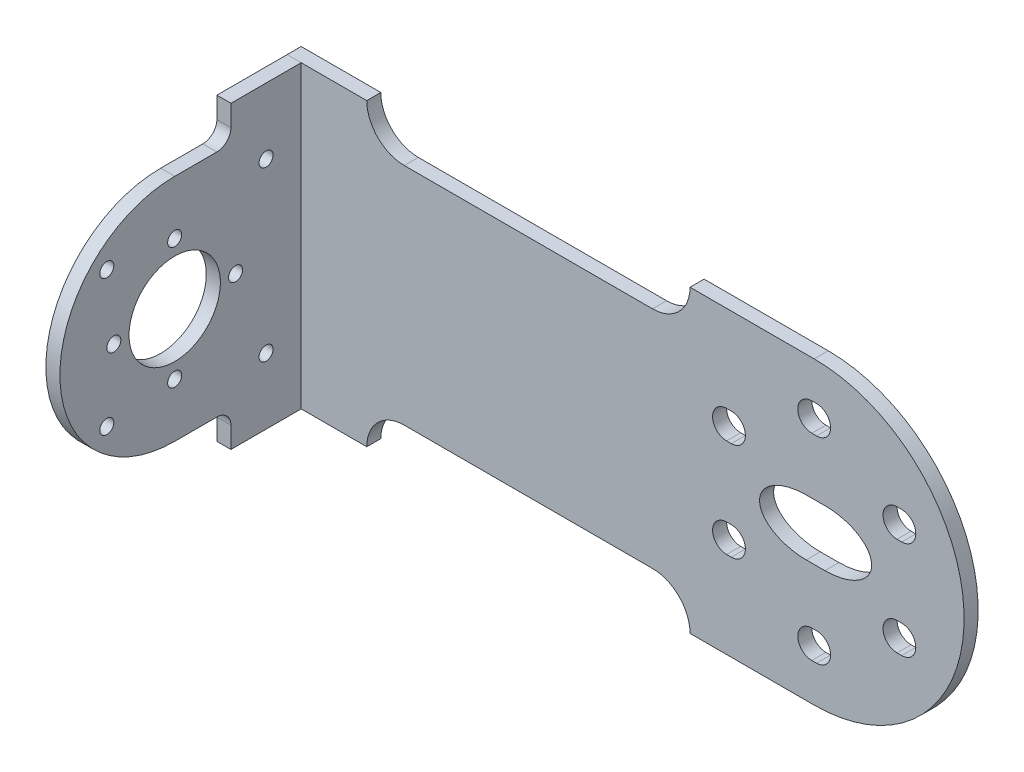
SolidWorks part; units mm, degrees
material "1060 Alloy"
ref_plane "Front Plane" through (0, 0, 0) normal (0, 0, 1) x (1, 0, 0)
ref_plane "Top Plane" through (0, 0, 0) normal (0, 1, 0) x (1, 0, 0)
ref_plane "Right Plane" through (0, 0, 0) normal (1, 0, 0) x (0, 0, -1)
sketch "Sketch1" plane through (0, 0, 0) normal (0, 0, 1) x (1, 0, 0)
  line L0 (-112.5, 32) -> (0, 32)
  line L1 (-112.5, -32) -> (0, -32)
  line L2 (17.6865, 10.5) -> (18.6865, 10.5) construction
  line L3 (-112.5, 32) -> (-112.5, -32)
  line L4 (-113, -33) -> (-113, 33) construction
  line L7 (17.6865, 13.5) -> (18.6865, 13.5)
  line L8 (17.6865, 7.5) -> (18.6865, 7.5)
  line L9 (17.6865, -10.5) -> (18.6865, -10.5) construction
  line L10 (17.6865, -7.5) -> (18.6865, -7.5)
  line L11 (17.6865, -13.5) -> (18.6865, -13.5)
  line L12 (-0.5, -21) -> (0.5, -21) construction
  line L13 (-0.5, -18) -> (0.5, -18)
  line L14 (-0.5, -24) -> (0.5, -24)
  line L15 (-18.6865, -10.5) -> (-17.6865, -10.5) construction
  line L16 (-18.6865, -7.5) -> (-17.6865, -7.5)
  line L17 (-18.6865, -13.5) -> (-17.6865, -13.5)
  line L18 (-17.6865, 10.5) -> (-18.6865, 10.5) construction
  line L19 (-17.6865, 7.5) -> (-18.6865, 7.5)
  line L20 (-17.6865, 13.5) -> (-18.6865, 13.5)
  line L21 (0.5, 21) -> (-0.5, 21) construction
  line L22 (0.5, 18) -> (-0.5, 18)
  line L23 (0.5, 24) -> (-0.5, 24)
  arc A1 (17.6865, 13.5) -> (17.6865, 7.5) centre (17.6865, 10.5) ccw
  circle A2 centre (18.1865, -10.5) radius 3 construction
  circle A3 centre (0, -21) radius 3 construction
  circle A4 centre (-18.1865, -10.5) radius 3 construction
  circle A5 centre (-18.1865, 10.5) radius 3 construction
  circle A6 centre (0, 21) radius 3 construction
  arc A7 (0, -32) -> (0, 32) centre (0, 0) ccw
  arc A11 (18.6865, 7.5) -> (18.6865, 13.5) centre (18.6865, 10.5) ccw
  circle A12 centre (18.1865, 10.5) radius 3 construction
  arc A13 (17.6865, -7.5) -> (17.6865, -13.5) centre (17.6865, -10.5) ccw
  arc A14 (18.6865, -13.5) -> (18.6865, -7.5) centre (18.6865, -10.5) ccw
  arc A15 (-0.5, -18) -> (-0.5, -24) centre (-0.5, -21) ccw
  arc A16 (0.5, -24) -> (0.5, -18) centre (0.5, -21) ccw
  arc A17 (-18.6865, -7.5) -> (-18.6865, -13.5) centre (-18.6865, -10.5) ccw
  arc A18 (-17.6865, -13.5) -> (-17.6865, -7.5) centre (-17.6865, -10.5) ccw
  arc A19 (-17.6865, 7.5) -> (-17.6865, 13.5) centre (-17.6865, 10.5) ccw
  arc A20 (-18.6865, 13.5) -> (-18.6865, 7.5) centre (-18.6865, 10.5) ccw
  arc A21 (0.5, 18) -> (0.5, 24) centre (0.5, 21) ccw
  arc A22 (-0.5, 24) -> (-0.5, 18) centre (-0.5, 21) ccw
  circle A23 centre (18.1865, -10.5) radius 3 construction
  circle A24 centre (0, -21) radius 3 construction
  circle A25 centre (-18.1865, -10.5) radius 3 construction
  circle A26 centre (-18.1865, 10.5) radius 3 construction
  circle A27 centre (0, 21) radius 3 construction
  arc A28 (0, -33) -> (0, 33) centre (0, 0) ccw construction
  point P3 (18.1865, 10.5)
  point P18 (0, 0)
  point P33 (18.1865, -10.5)
  point P41 (0, -21)
  point P48 (-18.1865, -10.5)
  point P56 (-18.1865, 10.5)
  point P62 (0, 21)
  dimension "D2" = 1
  dimension "D3" = 0.5
  dimension "D1" = 1
extrude "Boss-Extrude1" add sketch "Sketch1" along normal blind 3 contours A7 L0 L3 L1
sketch "Sketch2" plane through (-112.5, 0, 0) normal (-1, 0, 0) x (0, 0, 1)
  line L0 (3, -32) -> (18, -32)
  line L1 (18, -32) -> (18, -27.5)
  line L2 (21, -24.5) -> (30, -24.5)
  line L3 (0, 0) -> (46.5, 0) construction
  line L4 (3, 32) -> (18, 32)
  line L5 (18, 32) -> (18, 27.5)
  line L6 (21, 24.5) -> (30, 24.5)
  line L7 (44.4957, 14.4957) -> (30, 0) construction
  line L8 (54.5, 0) -> (46.5, 0) construction
  line L9 (17.8585, -11.1729) -> (3.1415, -24.7158) construction
  line L10 (17.8585, -11.1729) -> (30, 0) construction
  circle A0 centre (30, 0) radius 36.5 construction
  circle A2 centre (10.5, -17.9444) radius 1.5
  circle A3 centre (30, 13) radius 1.5
  circle A4 centre (30, 13) radius 1.5 construction
  circle A5 centre (43, 0) radius 1.5
  circle A6 centre (30, -13) radius 1.5
  circle A7 centre (17, 0) radius 1.5
  arc A11 (18, -27.5) -> (21, -24.5) centre (21, -27.5) cw
  arc A12 (18, 27.5) -> (21, 24.5) centre (21, 27.5) ccw
  circle A13 centre (10.5, 17.9444) radius 1.5
  arc A15 (27, -24.3156) -> (27, 24.3156) centre (30, 0) ccw construction
  arc A17 (30, -24.5) -> (30, 24.5) centre (30, 0) ccw
  circle A19 centre (30, 0) radius 16.5 construction
  circle A20 centre (30, 0) radius 20.5 construction
  circle A21 centre (30, 0) radius 36.5 construction
  circle A22 centre (44.4957, 14.4957) radius 1.5
  circle A23 centre (44.4957, -14.4957) radius 1.5
  circle A24 centre (30, 0) radius 9.75
  point P23 (50.5, 0)
  point P34 (30, 0)
  point P58 (10.5, -17.9444)
  point P62 (10.5, -32)
  dimension "D1" = 4
  dimension "D4" = 19.5
  dimension "D5" = 3
  dimension "D7" = 3
  dimension "D2" = 15
  dimension "D6" = 45
  dimension "D3" = 4
extrude "Boss-Extrude2" add sketch "Sketch2" against normal blind 3 separate body
ref_plane "Plane1" through (-68.3993, 0, -51.5425) normal (0.7986, 0, 0.6018) x (0, 1, 0)
sketch "Sketch3" plane through (-68.3993, 0, -51.5425) normal (0.7986, 0, 0.6018) x (0, 1, 0)
  circle A0 centre (0, 1.0136) radius 6
  circle A1 centre (0, 1.0136) radius 6 construction
extrude "Cut-Extrude1" cut sketch "Sketch3" along normal through all
sketch "Sketch4" plane through (0, 0, 3) normal (0, 0, 1) x (1, 0, 0)
  line L0 (2.2968, -6) -> (-1.6843, -6)
  line L2 (-1.6843, 6) -> (2.2968, 6)
  ellipse E0 centre (-1.6843, 0) end of major axis (-11.6542, 0) minor radius 6 (-1.6843, 6) -> (-1.6843, -6) ccw
  ellipse E1 centre (-1.6843, 0) end of major axis (-11.6542, 0) minor radius 6 construction
  ellipse E3 centre (2.2968, 0) end of major axis (12.2667, 0) minor radius 6 (2.2968, -6) -> (2.2968, 6) ccw
  ellipse E4 centre (2.2968, 0) end of major axis (-7.673, 0) minor radius 6 construction
extrude "Cut-Extrude2" cut sketch "Sketch4" against normal through all
sketch "Sketch5" plane through (0, 0, 3) normal (0, 0, 1) x (1, 0, 0)
  line L0 (-34.5, 32) -> (-87.5, 32) construction
  line L1 (-34.5, 24) -> (-87.5, 24)
  line L2 (-34.5, 40) -> (-87.5, 40)
  line L3 (-112.5, 32) -> (0, 32) construction
  line L4 (-112.5, 32) -> (-112.5, -32) construction
  line L5 (0, 0) -> (-112.5, 0) construction
  line L6 (-112.5, 24.5) -> (-112.5, -24.5) construction
  line L7 (-34.5, -32) -> (-87.5, -32) construction
  line L8 (-34.5, -24) -> (-87.5, -24)
  line L9 (-34.5, -40) -> (-87.5, -40)
  arc A2 (-34.5, 24) -> (-34.5, 40) centre (-34.5, 32) ccw
  arc A3 (-87.5, 40) -> (-87.5, 24) centre (-87.5, 32) ccw
  arc A4 (-34.5, -24) -> (-34.5, -40) centre (-34.5, -32) cw
  arc A5 (-87.5, -40) -> (-87.5, -24) centre (-87.5, -32) cw
  point P3 (-61, 32)
  point P19 (-61, -32)
  dimension "D1" = 8
  dimension "D2" = 25
  dimension "D3" = 53
extrude "Cut-Extrude3" cut sketch "Sketch5" against normal through all
